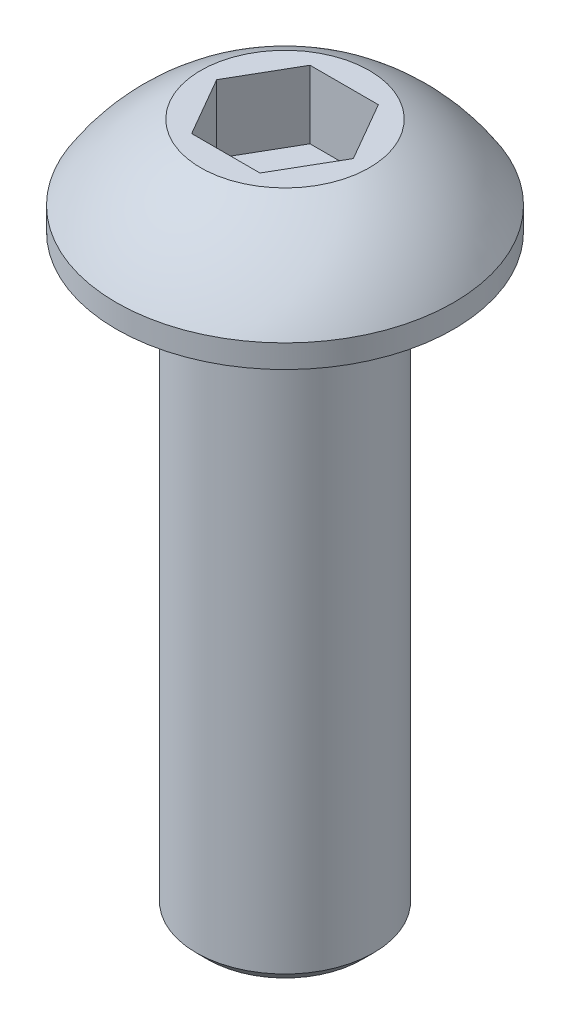
SolidWorks part; units mm, degrees
material "1023 Carbon Steel Sheet (SS)"
ref_plane "Front" through (0, 0, 0) normal (0, 0, 1) x (1, 0, 0)
ref_plane "Top" through (0, 0, 0) normal (0, 1, 0) x (1, 0, 0)
ref_plane "Right" through (0, 0, 0) normal (1, 0, 0) x (0, 0, -1)
sketch "Sketch1" plane through (0, 0, 0) normal (1, 0, 0) x (0, 0, -1)
  line L0 (0, 10.4571) -> (0, -14.5623) construction
  line L1 (0, 1.65) -> (0, -10)
  line L2 (0, -10) -> (1.3, -10)
  line L3 (1.5, -9.8) -> (1.5, -0.2)
  line L4 (1.7, 0) -> (2.85, 0)
  line L5 (2.85, 0) -> (2.85, 0.39)
  line L6 (0, 1.65) -> (1.425, 1.65)
  line L7 (1.5, -9.8) -> (1.3, -10)
  arc A0 (1.425, 1.65) -> (2.85, 0.39) centre (0, -1.3974) cw
  arc A1 (1.5, -0.2) -> (1.7, 0) centre (1.7, -0.2) cw
  dimension "D9" = 0.2
  dimension "D1" = 5.7
  dimension "D2" = 1.65
  dimension "D3" = 0.39
  dimension "D4" = 3
  dimension "D5" = 10
  dimension "D6" = 2.85
  dimension "D7" = 45
  dimension "D8" = 0.2
revolve "Revolve1" add sketch "Sketch1" angle 360 about L0
cosmetic thread "Cosmetic Thread1" parameters "D2"=2.439
sketch "Sketch2" plane through (0, 1.65, 0) normal (0, 1, 0) x (1, 0, 0)
  line L1 (0.5774, -1) -> (1.1547, 0)
  line L2 (1.1547, 0) -> (0.5774, 1)
  line L3 (0.5774, 1) -> (-0.5774, 1)
  line L4 (-0.5774, 1) -> (-1.1547, 0)
  line L5 (-1.1547, 0) -> (-0.5774, -1)
  line L6 (-0.5774, -1) -> (0.5774, -1)
  circle A0 centre (0, 0) radius 1 construction
  dimension "D1" = 2
extrude "Cut-Extrude1" cut sketch "Sketch2" against normal blind 1.15
equation "\"Screw Length\"= 10"
equation "\"D5@Sketch1\"=\"Screw Length\""
equation "\"End Chamfer\"= 0.2"
equation "\"Top Fillet\"= 0.2"
equation "\"Thread Length\"= \"Screw Length\" - \"End Chamfer\" - \"Top Fillet\""
equation "\"D8@Sketch1\"=\"End Chamfer\""
equation "\"D9@Sketch1\"=\"Top Fillet\""
